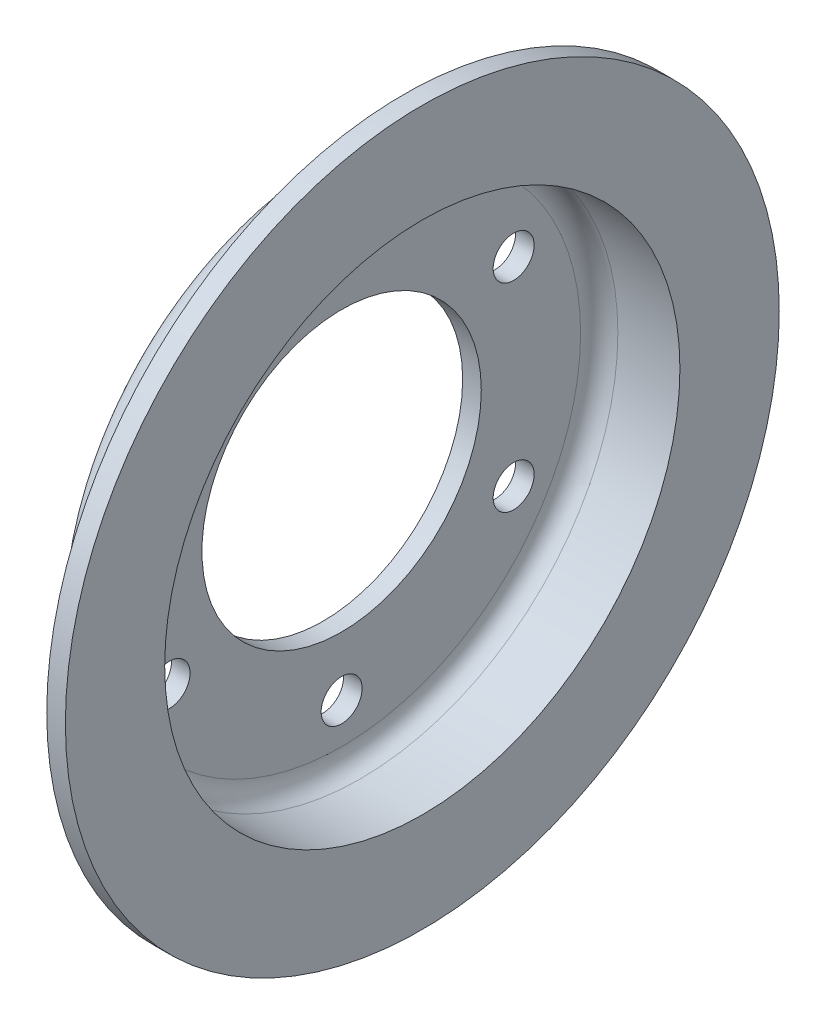
SolidWorks part; units mm, degrees
ref_plane "Front Plane" through (0, 0, 0) normal (0, 0, 1) x (1, 0, 0)
ref_plane "Top Plane" through (0, 0, 0) normal (0, 1, 0) x (1, 0, 0)
ref_plane "Right Plane" through (0, 0, 0) normal (1, 0, 0) x (0, 0, -1)
sketch "Sketch1" plane through (0, 0, 0) normal (1, 0, 0) x (0, 0, -1)
  circle A0 centre (0, 0) radius 44.5
  dimension "D1" = 89
extrude "Boss-Extrude2" add sketch "Sketch1" along normal blind 3
sketch "Sketch3" plane through (3, 0, 0) normal (1, 0, 0) x (0, 0, -1)
  circle A0 centre (0, 0) radius 44.5
  circle A1 centre (0, 0) radius 41.5
  dimension "D1" = 83
extrude "Boss-Extrude3" add sketch "Sketch3" along normal blind 10
sketch "Sketch4" plane through (13, 0, 0) normal (1, 0, 0) x (0, 0, -1)
  circle A0 centre (0, 0) radius 41.5
  circle A1 centre (0, 0) radius 57.5
  dimension "D1" = 115
extrude "Boss-Extrude4" add sketch "Sketch4" along normal blind 3
sketch "Sketch5" plane through (3, 0, 0) normal (1, 0, 0) x (0, 0, -1)
  circle A0 centre (0, 0) radius 22.5
  dimension "D1" = 45
extrude "Cut-Extrude1" cut sketch "Sketch5" against normal through all
fillet "Fillet1" radius 3 1 edges at (3, 0, -41.5)
sketch "Sketch6" plane through (0, 0, 0) normal (-1, 0, 0) x (0, 0, 1)
  circle A0 centre (0, 0) radius 32 construction
  dimension "D1" = 64
fillet "Fillet2" radius 5 1 edges at (0, 0, -44.5)
hole_wizard "Ø1.0mm Dowel Hole2" positions "Sketch10" profile "Sketch11" hole size "Ø1.0" standard "ISO" end condition through all
sketch "Sketch10" plane through (3, 0, 0) normal (1, 0, 0) x (0, 0, -1)
  circle A0 centre (0, 0) radius 32 construction
  point P0 (0, 32)
sketch "Sketch11" plane through (3, 32, 0) normal (0, 1, 0) x (0, 0, -1)
  line L0 (0, 0) -> (0, 3)
  line L1 (0, 3) -> (3.3, 3)
  line L2 (3.3, 3) -> (3.3, 0)
  line L5 (3.3, 0) -> (0, 0)
  line L11 (0, -6.35) -> (0, 107.95) construction
  dimension "Thru Hole Dia." = 6.6
  dimension "Thru Hole Depth" = 3
pattern_circular "CirPattern2" count 6 over 360 about axis through (0, 0, 0) along (1, 0, 0) of "Ø1.0mm Dowel Hole2"
